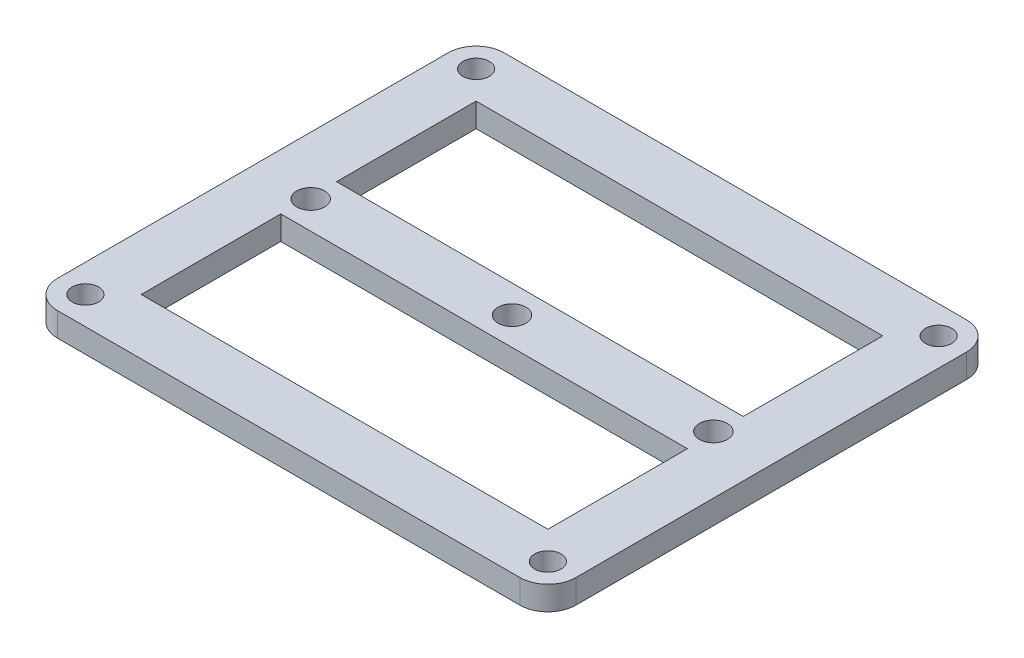
SolidWorks part; units mm, degrees
ref_plane "Front Plane" through (0, 0, 0) normal (0, 0, 1) x (1, 0, 0)
ref_plane "Top Plane" through (0, 0, 0) normal (0, 1, 0) x (1, 0, 0)
ref_plane "Right Plane" through (0, 0, 0) normal (1, 0, 0) x (0, 0, -1)
sketch "Sketch1" plane through (0, 0, 0) normal (0, 1, 0) x (1, 0, 0)
  line L0 (0, 49) -> (0, 0) construction
  line L1 (0, 0) -> (58, 0) construction
  line L2 (0, 49) -> (58, 49) construction
  line L3 (58, 49) -> (58, 0) construction
  line L4 (29, 0) -> (29, 49) construction
  line L5 (0, 24.5) -> (58, 24.5) construction
  line L8 (-3.5, -3.5) -> (-3.5, 52.5)
  line L11 (-3.5, 52.5) -> (61.5, 52.5)
  line L13 (54.5, 3.5) -> (54.5, 21)
  line L15 (61.5, -3.5) -> (61.5, 52.5)
  line L16 (3.5, 45.5) -> (54.5, 45.5)
  line L21 (3.5, 3.5) -> (54.5, 3.5)
  line L22 (3.5, 3.5) -> (3.5, 21)
  line L23 (-3.5, -3.5) -> (61.5, -3.5)
  line L24 (3.5, 28) -> (3.5, 45.5)
  line L27 (3.5, 28) -> (54.5, 28)
  line L29 (3.5, 21) -> (3.5, 3.5)
  line L30 (3.5, 21) -> (54.5, 21)
  line L31 (54.5, 28) -> (54.5, 45.5)
  line L32 (54.5, 21) -> (54.5, 3.5)
  line L33 (3.5, 3.5) -> (54.5, 3.5)
  circle A2 centre (0, 0) radius 1.65
  circle A4 centre (58, 0) radius 1.65
  circle A5 centre (58, 49) radius 1.65
  circle A6 centre (0, 49) radius 1.65
  point P18 (29, 24.5)
  dimension "D1" = 3.3
  dimension "D2" = 2
  dimension "D3" = 58
  dimension "D4" = 2
  dimension "D5" = 49
  dimension "D6" = 3.5
  dimension "D8" = 3.5
  dimension "D9" = 3.5
  dimension "D10" = 3.5
  dimension "D11" = 3.5
  dimension "D7" = 3.5
  dimension "D12" = 3.5
extrude "Boss-Extrude1" add sketch "Sketch1" along normal blind 3 contours L8 L23 L15 L11 A6 A5 A4 A2 L31 L27 L24 L16 L22 L30 L13 L21
fillet "Fillet1" radius 3.5 4 edges at (-3.5, 1.5, 3.5) (61.5, 1.5, 3.5) (61.5, 1.5, -52.5) (-3.5, 1.5, -52.5)
sketch "Sketch2" plane through (0, 3, 0) normal (0, 1, 0) x (1, 0, 0)
  line L0 (29, 28) -> (29, 21) construction
  line L1 (3.5, 28) -> (54.5, 28) construction
  line L2 (3.5, 21) -> (54.5, 21) construction
  line L3 (-3.5, 24.5) -> (61.5, 24.5) construction
  line L4 (-3.5, 0) -> (-3.5, 49) construction
  line L5 (61.5, 0) -> (61.5, 49) construction
  circle A0 centre (3.75, 24.5) radius 1.75
  circle A1 centre (29, 24.5) radius 1.75
  circle A2 centre (54.25, 24.5) radius 1.75
  dimension "D1" = 25.25
  dimension "D2" = 3.5
  dimension "D4" = 25.25
  dimension "D3" = 3
extrude "Cut-Extrude1" cut sketch "Sketch2" against normal up to next
